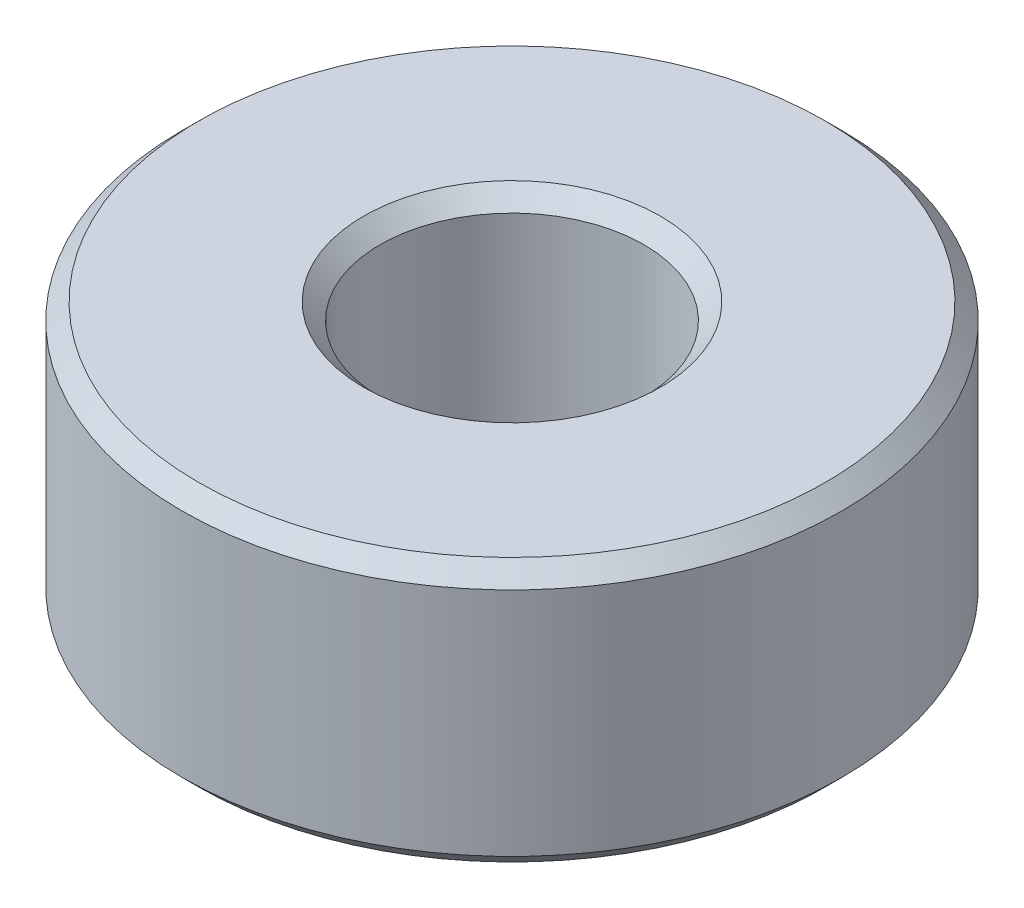
SolidWorks part; units mm, degrees
material "Duranickel(R) 301"
ref_plane "Front Plane" through (0, 0, 0) normal (0, 0, 1) x (1, 0, 0)
ref_plane "Top Plane" through (0, 0, 0) normal (0, 1, 0) x (1, 0, 0)
ref_plane "Right Plane" through (0, 0, 0) normal (1, 0, 0) x (0, 0, -1)
sketch "Sketch1" plane through (0, 0, 0) normal (0, 1, 0) x (1, 0, 0)
  circle A0 centre (0, 0) radius 2.5
  circle A1 centre (0, 0) radius 1
  dimension "D1" = 5
  dimension "D2" = 2
extrude "Boss-Extrude1" add sketch "Sketch1" along normal blind 2
chamfer "Chamfer1" distance 0.125 angle 45 4 edges at (0, 2, 1) (0, 2, 2.5) (0, 0, 1) (0, 0, 2.5)
